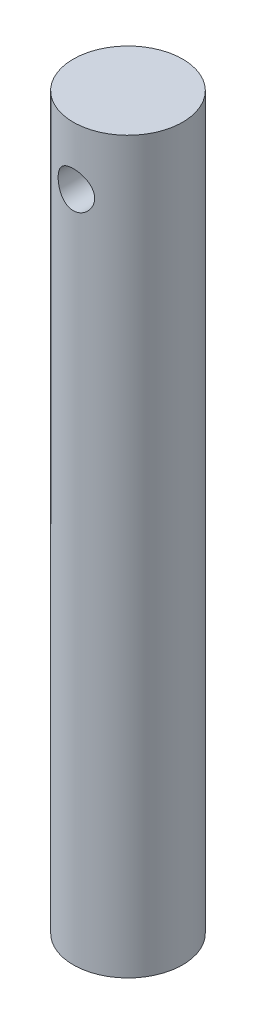
SolidWorks part; units mm, degrees
material "1060 Alloy"
ref_plane "Front Plane" through (0, 0, 0) normal (0, 0, 1) x (1, 0, 0)
ref_plane "Top Plane" through (0, 0, 0) normal (0, 1, 0) x (1, 0, 0)
ref_plane "Right Plane" through (0, 0, 0) normal (1, 0, 0) x (0, 0, -1)
sketch "Sketch2" plane through (0, 0, 0) normal (0, 0, 1) x (1, 0, 0)
  line L0 (0, 0) -> (0, -63.5)
  line L1 (0, 0) -> (4.76, 0)
  line L2 (0, 0) -> (0, -63.5) construction
  line L3 (0, -63.5) -> (4.76, -63.5)
  line L4 (4.76, 0) -> (4.76, -63.5)
  circle A0 centre (0, -5.08) radius 1.5875 construction
  dimension "D4" = 3.175
  dimension "D1" = 9.5199
  dimension "D2" = 5.08
  dimension "D3" = 63.5
revolve "Revolve1" add sketch "Sketch2" angle 360 about L2
sketch "Sketch3" plane through (0, 0, 0) normal (0, 0, 1) x (1, 0, 0)
  line L0 (0, -3.4925) -> (0, -6.6675) construction
  line L1 (0, 0) -> (4.7625, 0) construction
  line L2 (0, -3.4925) -> (0, -6.6675) construction
  line L3 (0, -63.5) -> (4.7625, -63.5) construction
  line L4 (4.7625, 0) -> (4.7625, -63.5) construction
  line L5 (0, 0) -> (0, -3.4925) construction
  line L6 (0, 0) -> (0, -3.4925) construction
  line L7 (0, -6.6675) -> (0, -63.5) construction
  line L8 (0, -6.6675) -> (0, -63.5) construction
  circle A0 centre (0, -5.08) radius 1.5875
  dimension "D4" = 3.175
  dimension "D1" = 4.7625
  dimension "D2" = 5.08
  dimension "D3" = 63.5
extrude "Cut-Extrude1" cut sketch "Sketch3" against normal through all both and the other way through all
